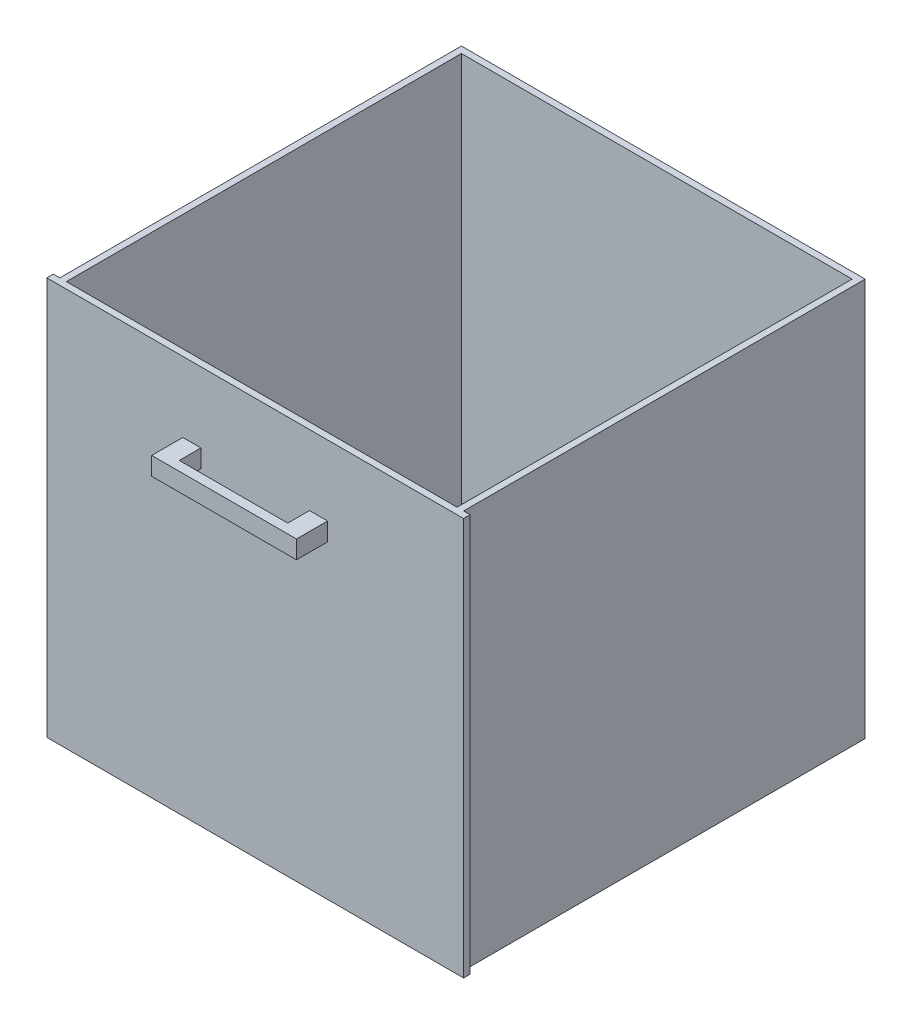
SolidWorks part; units mm, degrees
ref_plane "Front Plane" through (0, 0, 0) normal (0, 0, 1) x (1, 0, 0)
ref_plane "Top Plane" through (0, 0, 0) normal (0, 1, 0) x (1, 0, 0)
ref_plane "Right Plane" through (0, 0, 0) normal (1, 0, 0) x (0, 0, -1)
sketch "Sketch1" plane through (0, 0, 0) normal (0, 1, 0) x (1, 0, 0)
  line L0 (-382.121, -271.2802) -> (-373.121, -271.2802)
  line L1 (-373.121, 283.7198) -> (184.879, 283.7198)
  line L2 (-373.121, 283.7198) -> (-373.121, -271.2802)
  line L4 (184.879, 283.7198) -> (184.879, -271.2802)
  line L5 (-373.121, 283.7198) -> (184.879, -271.2802) construction
  line L6 (-373.121, -271.2802) -> (184.879, 283.7198) construction
  line L7 (193.879, -271.2802) -> (193.879, -280.2802)
  line L8 (193.879, -280.2802) -> (-382.121, -280.2802)
  line L9 (-382.121, -280.2802) -> (-382.121, -271.2802)
  line L10 (184.879, -271.2802) -> (193.879, -271.2802)
  point P0 (-94.121, 6.2198)
  point P8 (-94.121, -271.2802)
  dimension "D1" = 555
  dimension "D2" = 558
  dimension "D3" = 9
  dimension "D4" = 9
  dimension "D5" = 9
  dimension "D6" = 9
extrude "Boss-Extrude1" add sketch "Sketch1" along normal blind 550
sketch "Sketch3" plane through (0, 550, 0) normal (0, 1, 0) x (1, 0, 0)
  line L0 (-373.121, -271.2802) -> (184.879, -271.2802)
  line L1 (-364.121, 283.7198) -> (-364.121, -271.2802)
  line L2 (-364.121, 274.7198) -> (184.879, 274.7198)
  line L3 (175.879, 283.7198) -> (175.879, -271.2802)
  line L4 (-373.121, -271.2802) -> (-364.121, -271.2802)
  line L5 (-364.121, 283.7198) -> (-373.121, 283.7198)
  line L6 (-364.121, 274.7198) -> (-373.121, 274.7198)
  line L7 (-373.121, 283.7198) -> (-373.121, -271.2802) construction
  line L8 (193.879, -271.2802) -> (184.879, -271.2802)
  line L9 (184.879, -271.2802) -> (184.879, 283.7198)
  line L10 (184.879, 283.7198) -> (-373.121, 283.7198)
  line L11 (-373.121, 283.7198) -> (-373.121, -271.2802)
  line L12 (-373.121, -271.2802) -> (-382.121, -271.2802)
  line L13 (-382.121, -271.2802) -> (-382.121, -280.2802)
  line L14 (-382.121, -280.2802) -> (193.879, -280.2802)
  line L15 (193.879, -280.2802) -> (193.879, -271.2802)
  line L17 (184.879, 274.7198) -> (184.879, 283.7198)
  line L18 (184.879, 283.7198) -> (175.879, 283.7198)
  line L24 (-373.121, 274.7198) -> (-373.121, 283.7198)
  dimension "D2" = 9
  dimension "D3" = 9
  dimension "D4" = 9
  dimension "D1" = 0
extrude "Cut-Extrude1" cut sketch "Sketch3" against normal blind 545 contours L3 L2 L1 L0
sketch "Sketch4" plane through (0, 0, 280.2802) normal (0, 0, 1) x (1, 0, 0)
  line L0 (-94.121, 0) -> (-94.121, 550) construction
  line L1 (-382.121, 0) -> (193.879, 0) construction
  line L2 (-382.121, 550) -> (193.879, 550) construction
  line L3 (-382.121, 275) -> (193.879, 275) construction
  line L4 (-382.121, 550) -> (-382.121, 0) construction
  line L5 (193.879, 550) -> (193.879, 0) construction
  line L7 (-194.121, 452.9682) -> (5.879, 452.9682)
  line L8 (-194.121, 452.9682) -> (-194.121, 427.9682)
  line L9 (-194.121, 427.9682) -> (5.879, 427.9682)
  line L10 (5.879, 452.9682) -> (5.879, 427.9682)
  line L11 (-194.121, 452.9682) -> (5.879, 427.9682) construction
  line L12 (-194.121, 427.9682) -> (5.879, 452.9682) construction
  point P12 (-94.121, 440.4682)
  dimension "D1" = 200
  dimension "D2" = 25
extrude "Boss-Extrude2" add sketch "Sketch4" along normal blind 43
sketch "Sketch6" plane through (0, 452.9682, 0) normal (0, 1, 0) x (1, 0, 0)
  line L0 (-169.121, -280.2802) -> (-19.121, -280.2802)
  line L1 (-382.121, -280.2802) -> (193.879, -280.2802) construction
  line L2 (-169.121, -280.2802) -> (-169.121, -310.2802)
  line L3 (-94.121, -323.2802) -> (-94.121, -280.2802) construction
  line L5 (5.879, -323.2802) -> (-194.121, -323.2802) construction
  line L6 (-19.121, -280.2802) -> (-19.121, -310.2802)
  line L7 (-169.121, -310.2802) -> (-19.121, -310.2802)
  dimension "D1" = 150
  dimension "D2" = 30
extrude "Cut-Extrude2" cut sketch "Sketch6" against normal blind 25 contours L0 L6 L7 L2
